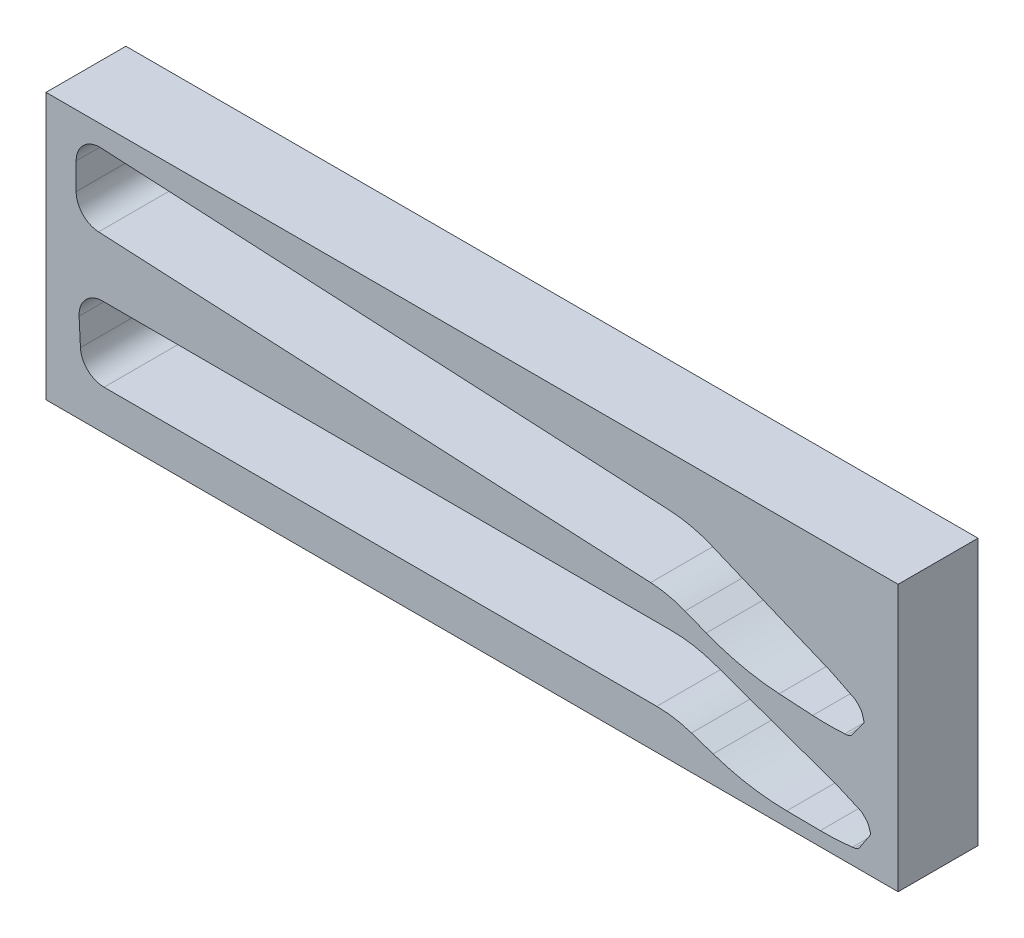
SolidWorks part; units mm, degrees
ref_plane "Front Plane" through (0, 0, 0) normal (0, 0, 1) x (1, 0, 0)
ref_plane "Top Plane" through (0, 0, 0) normal (0, 1, 0) x (1, 0, 0)
ref_plane "Right Plane" through (0, 0, 0) normal (1, 0, 0) x (0, 0, -1)
sketch "Sketch1" plane through (0, 0, 0) normal (0, 0, 1) x (1, 0, 0)
  line L2 (-16, 5) -> (-16, -5)
  line L3 (-16, -5) -> (16, -5)
  line L4 (16, 5) -> (16, -5)
  line L5 (-16, 5) -> (16, -5) construction
  line L6 (-16, -5) -> (16, 5) construction
  line L18 (-16, 5) -> (16, 5)
  point P0 (0, 0)
  line B0 (7.5082, -0.7616) -> (-13.8672, -0.7242)
  line B1 (6.9371, -3.5) -> (-13.8187, -3.5)
  line B2 (-14.7566, -1.6577) -> (-14.7066, -2.6555)
  line B3 (13.6884, -2.6726) -> (9.0977, -1.0376)
  line B4 (9.0523, -3.9896) -> (8.2405, -3.7147)
  line B5 (13.0783, -4.471) -> (11.8175, -4.4588)
  line B6 (14.9628, -3.6663) -> (14.5542, -4.2837)
  line B7 (14.798, -3.2503) -> (14.6809, -3.1341)
  line B8 (14.5651, -3.0554) -> (13.6884, -2.6726)
  line B9 (14.9684, -3.6215) -> (14.8893, -3.3951)
  line B10 (14.372, -4.3958) -> (14.2834, -4.4062)
  arc B11 (-14.7566, -1.6577) -> (-13.8672, -0.7242) centre (-13.8688, -1.6132) cw
  arc B12 (-14.7066, -2.6555) -> (-13.8187, -3.5) centre (-13.8187, -2.611) ccw
  arc B13 (9.0523, -3.9896) -> (11.8175, -4.4588) centre (11.9036, 4.4308) ccw
  arc B14 (8.2405, -3.7147) -> (6.9371, -3.5) centre (6.9371, -7.564) ccw
  arc B15 (9.0977, -1.0376) -> (7.5082, -0.7616) centre (7.4998, -5.5241) ccw
  arc B16 (14.8893, -3.3951) -> (14.798, -3.2503) centre (14.5296, -3.5207) ccw
  arc B17 (14.5651, -3.0554) -> (14.6809, -3.1341) centre (14.4126, -3.4046) cw
  arc B18 (14.9684, -3.6215) -> (14.9628, -3.6663) centre (14.9204, -3.6382) cw
  arc B19 (14.372, -4.3958) -> (14.5542, -4.2837) centre (14.3424, -4.1436) ccw
  arc B20 (14.2834, -4.4062) -> (13.0783, -4.471) centre (13.1706, 5.0535) cw
  line B21 (7.4135, 3.116) -> (-13.9332, 4.2243)
  line B22 (6.7059, 0.4097) -> (-14.0238, 1.4495)
  line B23 (-14.8683, 3.3365) -> (-14.8683, 2.3374)
  line B24 (13.4902, 0.8978) -> (8.9872, 2.7607)
  line B25 (8.794, -0.1853) -> (7.997, 0.13)
  line B26 (12.7908, -0.8678) -> (11.5322, -0.7924)
  line B27 (14.7132, -0.1585) -> (14.2742, -0.7547)
  line B28 (14.5695, 0.2653) -> (14.4584, 0.3871)
  line B29 (14.3466, 0.4715) -> (13.4902, 0.8978)
  line B30 (14.7211, -0.114) -> (14.6534, 0.1161)
  line B31 (14.0867, -0.8575) -> (13.9976, -0.8635)
  arc B32 (-14.8683, 3.3365) -> (-13.9332, 4.2243) centre (-13.9793, 3.3365) cw
  arc B33 (-14.8683, 2.3374) -> (-14.0238, 1.4495) centre (-13.9793, 2.3374) ccw
  arc B34 (8.794, -0.1853) -> (11.5322, -0.7924) centre (12.0635, 8.0817) ccw
  arc B35 (7.997, 0.13) -> (6.7059, 0.4097) centre (6.5023, -3.6492) ccw
  arc B36 (8.9872, 2.7607) -> (7.4135, 3.116) centre (7.1666, -1.6401) ccw
  arc B37 (14.6534, 0.1161) -> (14.5695, 0.2653) centre (14.2879, 0.0086) ccw
  arc B38 (14.3466, 0.4715) -> (14.4584, 0.3871) centre (14.1768, 0.1305) cw
  arc B39 (14.7211, -0.114) -> (14.7132, -0.1585) centre (14.6723, -0.1283) cw
  arc B40 (14.0867, -0.8575) -> (14.2742, -0.7547) centre (14.0697, -0.6041) ccw
  arc B41 (13.9976, -0.8635) -> (12.7908, -0.8678) centre (13.3601, 8.6402) cw
  dimension "D1" = 32
  dimension "D2" = 10
  dimension "D3" = 1.5
sketch_block_instance "ScanOutline-1"
sketch_block "ScanOutline" parameters "D1"=0.889, "D2"=8.89, "D3"=4.064, "D4"=4.7625, "D5"=0.381, "D6"=0.0508, "D7"=0.254, "D8"=9.525
sketch_block_instance "ScanOutline-3"
extrude "Boss-Extrude1" add sketch "Sketch1" along normal blind 3
